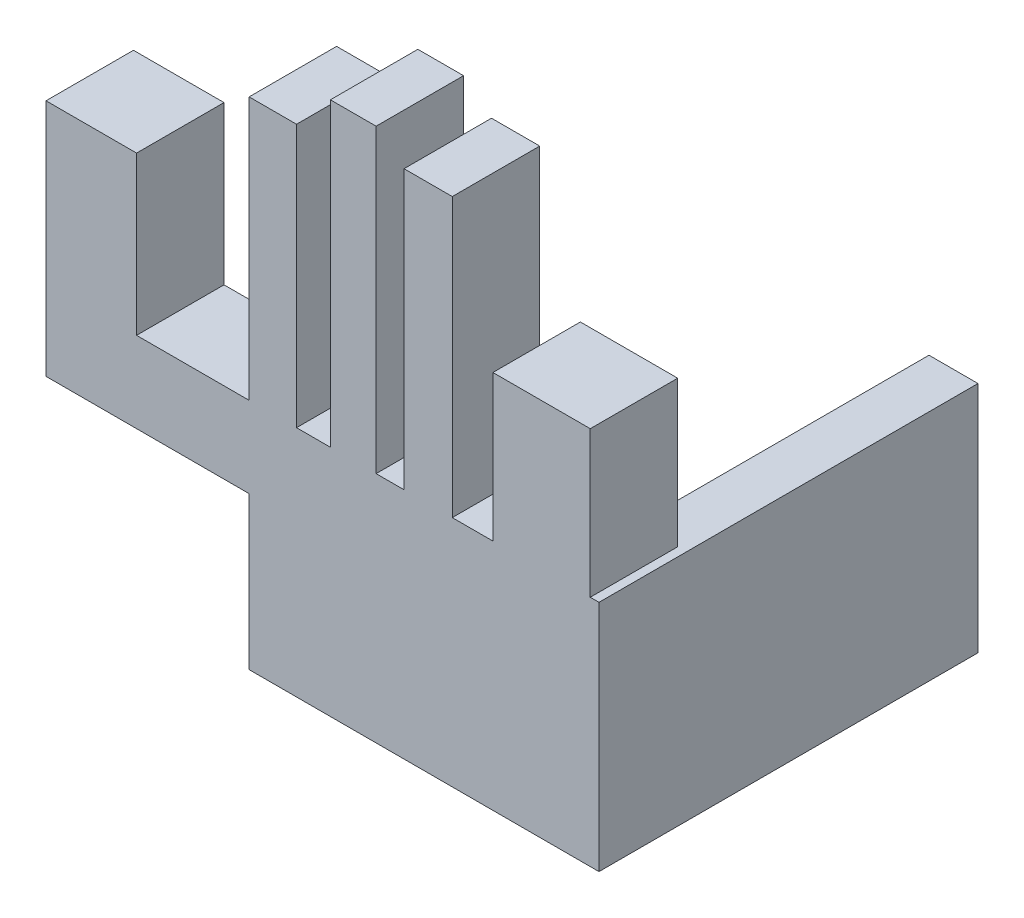
SolidWorks part; units mm, degrees
ref_plane "Front Plane" through (0, 0, 0) normal (0, 0, 1) x (1, 0, 0)
ref_plane "Top Plane" through (0, 0, 0) normal (0, 1, 0) x (1, 0, 0)
ref_plane "Right Plane" through (0, 0, 0) normal (1, 0, 0) x (0, 0, -1)
sketch "Sketch1" plane through (0, 0, 0) normal (0, 0, 1) x (1, 0, 0)
  line L0 (21.7742, 0) -> (26.5645, 0)
  line L1 (8.129, 0) -> (13.9355, 0)
  line L2 (0, -13.8629) -> (0, -40)
  line L3 (0, -40) -> (60, -40)
  line L4 (60, 0) -> (60, -40)
  line L5 (0, 0) -> (-19.3065, 0)
  line L7 (0, -13.8629) -> (-34.8387, -13.8629)
  line L8 (-34.8387, 0) -> (-34.8387, -13.8629)
  line L10 (-34.8387, 0) -> (-34.8387, 27.0726)
  line L11 (-34.8387, 27.0726) -> (-19.3065, 27.0726)
  line L12 (-19.3065, 0) -> (-19.3065, 27.0726)
  line L14 (0, 0) -> (0, 45.0726)
  line L15 (0, 45.0726) -> (8.129, 45.0726)
  line L16 (8.129, 0) -> (8.129, 45.0726)
  line L18 (13.9355, 0) -> (13.9355, 51.6048)
  line L19 (13.9355, 51.6048) -> (21.7742, 51.6048)
  line L20 (21.7742, 0) -> (21.7742, 51.6048)
  line L26 (26.5645, 0) -> (26.5645, 47.6855)
  line L27 (26.5645, 47.6855) -> (34.8387, 47.6855)
  line L28 (34.8387, 0) -> (34.8387, 47.6855)
  line L30 (41.8065, 0) -> (41.8065, 25.0403)
  line L31 (41.8065, 25.0403) -> (58.5, 25.0403)
  line L32 (58.5, 0) -> (58.5, 25.0403)
  line L33 (34.8387, 0) -> (41.8065, 0)
  line L34 (58.5, 0) -> (60, 0)
  dimension "D1" = 60
  dimension "D2" = 40
extrude "Boss-Extrude1" add sketch "Sketch1" along normal blind 15
sketch "Sketch2" plane through (0, 0, 0) normal (0, 0, -1) x (-1, 0, 0)
  line L0 (0, -40) -> (-60, -40) construction
  line L1 (-60, 0) -> (-51.5955, 0)
  line L2 (-60, 0) -> (-60, -40)
  line L3 (-60, -40) -> (-51.5955, -40)
  line L4 (-51.5955, 0) -> (-51.5955, -40)
extrude "Boss-Extrude2" add sketch "Sketch2" along normal blind 50
sketch "Sketch3" plane through (51.5955, 0, 0) normal (-1, 0, 0) x (0, 0, 1)
  line L1 (-35.3005, -16.0825) -> (-15.3005, -16.0825)
  line L2 (-35.3005, -16.0825) -> (-35.3005, -22.0825)
  line L3 (-35.3005, -22.0825) -> (-15.3005, -22.0825)
  line L4 (-15.3005, -16.0825) -> (-15.3005, -22.0825)
  dimension "D1" = 20
  dimension "D2" = 6
extrude "Cut-Extrude1" cut sketch "Sketch3" against normal blind 2
